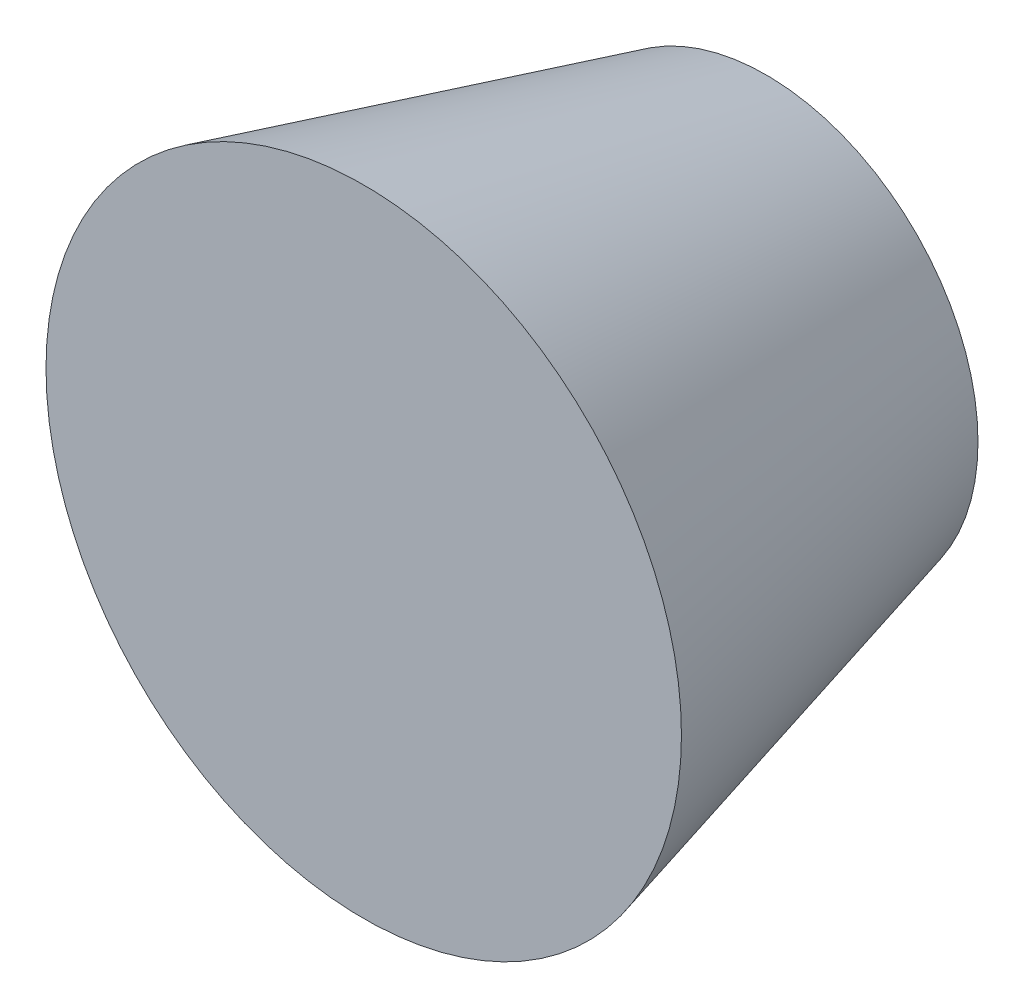
SolidWorks part; units mm, degrees
ref_plane "前视基准面" through (0, 0, 0) normal (0, 0, 1) x (1, 0, 0)
ref_plane "上视基准面" through (0, 0, 0) normal (0, 1, 0) x (1, 0, 0)
ref_plane "右视基准面" through (0, 0, 0) normal (1, 0, 0) x (0, 0, -1)
sketch "草图1" plane through (0, 0, 0) normal (0, 0, 1) x (1, 0, 0)
  circle A0 centre (0, 0) radius 10
sketch "草图2" plane through (0, 0, 0) normal (0, 1, 0) x (1, 0, 0)
  line L0 (0, 0) -> (0, -19)
ref_plane "基准面1" through (0, 0, 19) normal (0, 0, 1) x (1, 0, 0)
sketch "草图3" plane through (0, 0, 19) normal (0, 0, 1) x (1, 0, 0)
  circle A0 centre (0, 0) radius 15
sketch "草图4" plane through (0, 0, 0) normal (0, 1, 0) x (1, 0, 0)
  line L0 (-10, 0) -> (-15, -19)
  line L1 (-10, 0) -> (10, 0) construction
  line L2 (-15, -19) -> (15, -19) construction
loft "放样1" add profiles "草图1", "草图3"
